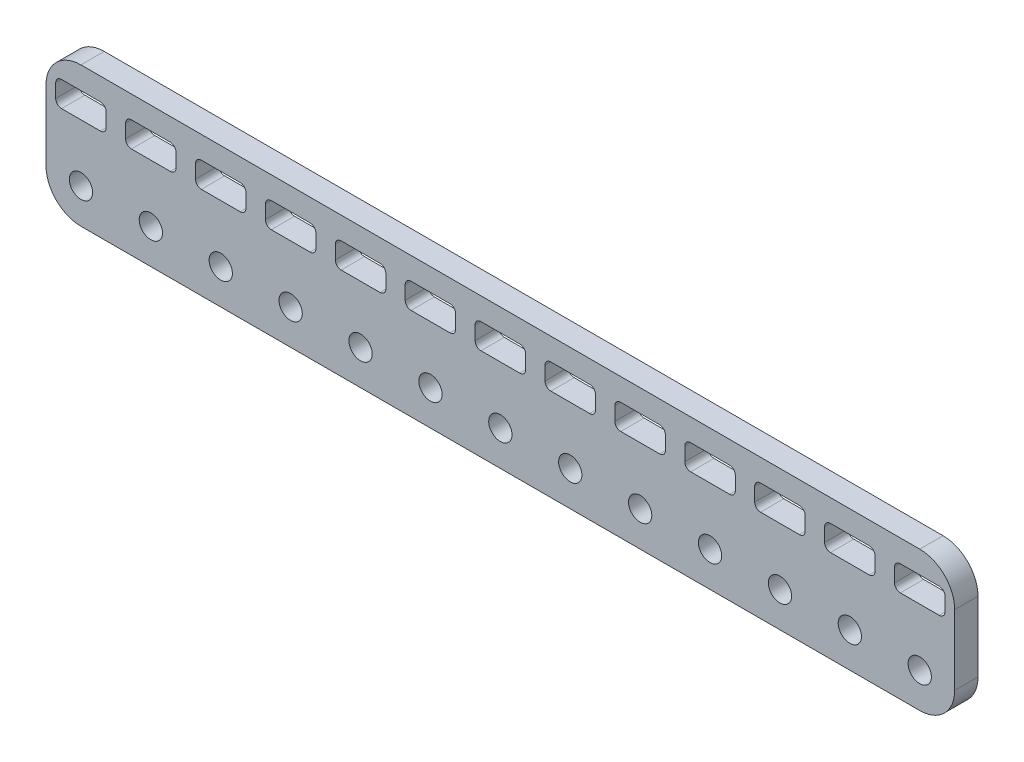
SolidWorks part; units mm, degrees
ref_plane "Alzado" through (0, 0, 0) normal (0, 0, 1) x (1, 0, 0)
ref_plane "Planta" through (0, 0, 0) normal (0, 1, 0) x (1, 0, 0)
ref_plane "Vista lateral" through (0, 0, 0) normal (1, 0, 0) x (0, 0, -1)
sketch "Model" plane through (0, 0, 0) normal (0, 0, 1) x (1, 0, 0)
  line L0 (256.4291, 228.7422) -> (364.4291, 228.7422)
  line L1 (364.4291, 210.7422) -> (256.4291, 210.7422)
  line L2 (368.9291, 224.2422) -> (368.9291, 215.2422)
  line L3 (251.9291, 224.2422) -> (251.9291, 215.2422)
  line L4 (267.9291, 222.6172) -> (262.9291, 222.6172)
  line L5 (262.1791, 223.3672) -> (262.1791, 225.1172)
  line L6 (262.9291, 225.8672) -> (267.9291, 225.8672)
  line L7 (268.6791, 225.1172) -> (268.6791, 223.3672)
  line L8 (285.9291, 222.6172) -> (280.9291, 222.6172)
  line L9 (280.1791, 223.3672) -> (280.1791, 225.1172)
  line L10 (280.9291, 225.8672) -> (285.9291, 225.8672)
  line L11 (286.6791, 225.1172) -> (286.6791, 223.3672)
  line L12 (258.9291, 222.6172) -> (253.9291, 222.6172)
  line L13 (253.1791, 223.3672) -> (253.1791, 225.1172)
  line L14 (253.9291, 225.8672) -> (258.9291, 225.8672)
  line L15 (259.6791, 225.1172) -> (259.6791, 223.3672)
  line L16 (276.9291, 222.6172) -> (271.9291, 222.6172)
  line L17 (271.1791, 223.3672) -> (271.1791, 225.1172)
  line L18 (271.9291, 225.8672) -> (276.9291, 225.8672)
  line L19 (277.6791, 225.1172) -> (277.6791, 223.3672)
  line L20 (294.9291, 222.6172) -> (289.9291, 222.6172)
  line L21 (289.1791, 223.3672) -> (289.1791, 225.1172)
  line L22 (289.9291, 225.8672) -> (294.9291, 225.8672)
  line L23 (295.6791, 225.1172) -> (295.6791, 223.3672)
  line L24 (303.9291, 222.6172) -> (298.9291, 222.6172)
  line L25 (298.1791, 223.3672) -> (298.1791, 225.1172)
  line L26 (298.9291, 225.8672) -> (303.9291, 225.8672)
  line L27 (304.6791, 225.1172) -> (304.6791, 223.3672)
  line L28 (321.9291, 222.6172) -> (316.9291, 222.6172)
  line L29 (316.1791, 223.3672) -> (316.1791, 225.1172)
  line L30 (316.9291, 225.8672) -> (321.9291, 225.8672)
  line L31 (322.6791, 225.1172) -> (322.6791, 223.3672)
  line L32 (312.9291, 222.6172) -> (307.9291, 222.6172)
  line L33 (307.1791, 223.3672) -> (307.1791, 225.1172)
  line L34 (307.9291, 225.8672) -> (312.9291, 225.8672)
  line L35 (313.6791, 225.1172) -> (313.6791, 223.3672)
  line L36 (357.9291, 222.6172) -> (352.9291, 222.6172)
  line L37 (352.1791, 223.3672) -> (352.1791, 225.1172)
  line L38 (352.9291, 225.8672) -> (357.9291, 225.8672)
  line L39 (358.6791, 225.1172) -> (358.6791, 223.3672)
  line L40 (348.9291, 222.6172) -> (343.9291, 222.6172)
  line L41 (343.1791, 223.3672) -> (343.1791, 225.1172)
  line L42 (343.9291, 225.8672) -> (348.9291, 225.8672)
  line L43 (349.6791, 225.1172) -> (349.6791, 223.3672)
  line L44 (339.9291, 222.6172) -> (334.9291, 222.6172)
  line L45 (334.1791, 223.3672) -> (334.1791, 225.1172)
  line L46 (334.9291, 225.8672) -> (339.9291, 225.8672)
  line L47 (340.6791, 225.1172) -> (340.6791, 223.3672)
  line L48 (330.9291, 222.6172) -> (325.9291, 222.6172)
  line L49 (325.1791, 223.3672) -> (325.1791, 225.1172)
  line L50 (325.9291, 225.8672) -> (330.9291, 225.8672)
  line L51 (331.6791, 225.1172) -> (331.6791, 223.3672)
  line L52 (366.9291, 222.6172) -> (361.9291, 222.6172)
  line L53 (361.1791, 223.3672) -> (361.1791, 225.1172)
  line L54 (361.9291, 225.8672) -> (366.9291, 225.8672)
  line L55 (367.6791, 225.1172) -> (367.6791, 223.3672)
  arc A0 (368.9291, 224.2422) -> (364.4291, 228.7422) centre (364.4291, 224.2422) ccw
  arc A1 (256.4291, 228.7422) -> (251.9291, 224.2422) centre (256.4291, 224.2422) ccw
  arc A2 (251.9291, 215.2422) -> (256.4291, 210.7422) centre (256.4291, 215.2422) ccw
  arc A3 (364.4291, 210.7422) -> (368.9291, 215.2422) centre (364.4291, 215.2422) ccw
  circle A4 centre (337.4291, 215.2422) radius 1.5
  circle A5 centre (319.4291, 215.2422) radius 1.5
  circle A6 centre (328.4291, 215.2422) radius 1.5
  circle A7 centre (310.4291, 215.2422) radius 1.5
  circle A8 centre (292.4291, 215.2422) radius 1.5
  circle A9 centre (301.4291, 215.2422) radius 1.5
  circle A10 centre (274.4291, 215.2422) radius 1.5
  circle A11 centre (283.4291, 215.2422) radius 1.5
  circle A12 centre (265.4291, 215.2422) radius 1.5
  circle A13 centre (256.4291, 215.2422) radius 1.5
  circle A14 centre (346.4291, 215.2422) radius 1.5
  circle A15 centre (355.4291, 215.2422) radius 1.5
  arc A16 (262.1791, 223.3672) -> (262.9291, 222.6172) centre (262.9291, 223.3672) ccw
  arc A17 (262.9291, 225.8672) -> (262.1791, 225.1172) centre (262.9291, 225.1172) ccw
  arc A18 (268.6791, 225.1172) -> (267.9291, 225.8672) centre (267.9291, 225.1172) ccw
  arc A19 (267.9291, 222.6172) -> (268.6791, 223.3672) centre (267.9291, 223.3672) ccw
  arc A20 (280.1791, 223.3672) -> (280.9291, 222.6172) centre (280.9291, 223.3672) ccw
  arc A21 (280.9291, 225.8672) -> (280.1791, 225.1172) centre (280.9291, 225.1172) ccw
  arc A22 (286.6791, 225.1172) -> (285.9291, 225.8672) centre (285.9291, 225.1172) ccw
  arc A23 (285.9291, 222.6172) -> (286.6791, 223.3672) centre (285.9291, 223.3672) ccw
  arc A24 (253.1791, 223.3672) -> (253.9291, 222.6172) centre (253.9291, 223.3672) ccw
  arc A25 (253.9291, 225.8672) -> (253.1791, 225.1172) centre (253.9291, 225.1172) ccw
  arc A26 (259.6791, 225.1172) -> (258.9291, 225.8672) centre (258.9291, 225.1172) ccw
  arc A27 (258.9291, 222.6172) -> (259.6791, 223.3672) centre (258.9291, 223.3672) ccw
  arc A28 (271.1791, 223.3672) -> (271.9291, 222.6172) centre (271.9291, 223.3672) ccw
  arc A29 (271.9291, 225.8672) -> (271.1791, 225.1172) centre (271.9291, 225.1172) ccw
  arc A30 (277.6791, 225.1172) -> (276.9291, 225.8672) centre (276.9291, 225.1172) ccw
  arc A31 (276.9291, 222.6172) -> (277.6791, 223.3672) centre (276.9291, 223.3672) ccw
  arc A32 (289.1791, 223.3672) -> (289.9291, 222.6172) centre (289.9291, 223.3672) ccw
  arc A33 (289.9291, 225.8672) -> (289.1791, 225.1172) centre (289.9291, 225.1172) ccw
  arc A34 (295.6791, 225.1172) -> (294.9291, 225.8672) centre (294.9291, 225.1172) ccw
  arc A35 (294.9291, 222.6172) -> (295.6791, 223.3672) centre (294.9291, 223.3672) ccw
  arc A36 (298.1791, 223.3672) -> (298.9291, 222.6172) centre (298.9291, 223.3672) ccw
  arc A37 (298.9291, 225.8672) -> (298.1791, 225.1172) centre (298.9291, 225.1172) ccw
  arc A38 (304.6791, 225.1172) -> (303.9291, 225.8672) centre (303.9291, 225.1172) ccw
  arc A39 (303.9291, 222.6172) -> (304.6791, 223.3672) centre (303.9291, 223.3672) ccw
  arc A40 (316.1791, 223.3672) -> (316.9291, 222.6172) centre (316.9291, 223.3672) ccw
  arc A41 (316.9291, 225.8672) -> (316.1791, 225.1172) centre (316.9291, 225.1172) ccw
  arc A42 (322.6791, 225.1172) -> (321.9291, 225.8672) centre (321.9291, 225.1172) ccw
  arc A43 (321.9291, 222.6172) -> (322.6791, 223.3672) centre (321.9291, 223.3672) ccw
  arc A44 (307.1791, 223.3672) -> (307.9291, 222.6172) centre (307.9291, 223.3672) ccw
  arc A45 (307.9291, 225.8672) -> (307.1791, 225.1172) centre (307.9291, 225.1172) ccw
  arc A46 (313.6791, 225.1172) -> (312.9291, 225.8672) centre (312.9291, 225.1172) ccw
  arc A47 (312.9291, 222.6172) -> (313.6791, 223.3672) centre (312.9291, 223.3672) ccw
  arc A48 (352.1791, 223.3672) -> (352.9291, 222.6172) centre (352.9291, 223.3672) ccw
  arc A49 (352.9291, 225.8672) -> (352.1791, 225.1172) centre (352.9291, 225.1172) ccw
  arc A50 (358.6791, 225.1172) -> (357.9291, 225.8672) centre (357.9291, 225.1172) ccw
  arc A51 (357.9291, 222.6172) -> (358.6791, 223.3672) centre (357.9291, 223.3672) ccw
  arc A52 (343.1791, 223.3672) -> (343.9291, 222.6172) centre (343.9291, 223.3672) ccw
  arc A53 (343.9291, 225.8672) -> (343.1791, 225.1172) centre (343.9291, 225.1172) ccw
  arc A54 (349.6791, 225.1172) -> (348.9291, 225.8672) centre (348.9291, 225.1172) ccw
  arc A55 (348.9291, 222.6172) -> (349.6791, 223.3672) centre (348.9291, 223.3672) ccw
  arc A56 (334.1791, 223.3672) -> (334.9291, 222.6172) centre (334.9291, 223.3672) ccw
  arc A57 (334.9291, 225.8672) -> (334.1791, 225.1172) centre (334.9291, 225.1172) ccw
  arc A58 (340.6791, 225.1172) -> (339.9291, 225.8672) centre (339.9291, 225.1172) ccw
  arc A59 (339.9291, 222.6172) -> (340.6791, 223.3672) centre (339.9291, 223.3672) ccw
  arc A60 (325.1791, 223.3672) -> (325.9291, 222.6172) centre (325.9291, 223.3672) ccw
  arc A61 (325.9291, 225.8672) -> (325.1791, 225.1172) centre (325.9291, 225.1172) ccw
  arc A62 (331.6791, 225.1172) -> (330.9291, 225.8672) centre (330.9291, 225.1172) ccw
  arc A63 (330.9291, 222.6172) -> (331.6791, 223.3672) centre (330.9291, 223.3672) ccw
  circle A64 centre (364.4291, 215.2422) radius 1.5
  arc A65 (361.1791, 223.3672) -> (361.9291, 222.6172) centre (361.9291, 223.3672) ccw
  arc A66 (361.9291, 225.8672) -> (361.1791, 225.1172) centre (361.9291, 225.1172) ccw
  arc A67 (367.6791, 225.1172) -> (366.9291, 225.8672) centre (366.9291, 225.1172) ccw
  arc A68 (366.9291, 222.6172) -> (367.6791, 223.3672) centre (366.9291, 223.3672) ccw
extrude "Saliente-Extruir1" add sketch "Model" along normal blind 3
